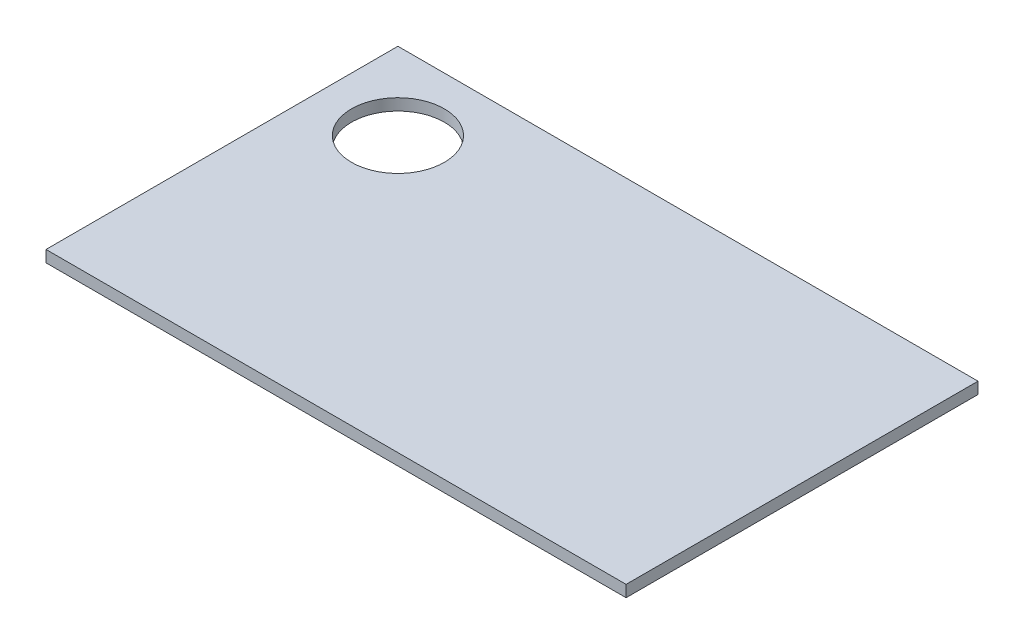
SolidWorks part; units mm, degrees
ref_plane "Front Plane" through (0, 0, 0) normal (0, 0, 1) x (1, 0, 0)
ref_plane "Top Plane" through (0, 0, 0) normal (0, 1, 0) x (1, 0, 0)
ref_plane "Right Plane" through (0, 0, 0) normal (1, 0, 0) x (0, 0, -1)
sketch "Sketch3" plane through (0, 711.2, 0) normal (0, 1, 0) x (1, 0, 0)
  line L0 (-476.25, 298.45) -> (-476.25, -285.75) construction
  line L2 (476.25, 298.45) -> (476.25, -285.75) construction
  line L3 (-476.25, 298.45) -> (476.25, 298.45) construction
  line L4 (-476.25, 298.45) -> (-476.25, -279.4)
  line L5 (-476.25, -279.4) -> (476.25, -279.4)
  line L6 (476.25, 298.45) -> (476.25, -279.4)
  line L7 (-476.25, 298.45) -> (476.25, 298.45)
  line L9 (-438.15, -279.4) -> (-476.25, -279.4) construction
extrude "Boss-Extrude2" add sketch "Sketch3" against normal blind 19.05
sketch "Sketch4" plane through (0, 711.2, 0) normal (0, 1, 0) x (1, 0, 0)
  line L0 (476.25, 298.45) -> (-476.25, 298.45) construction
  line L1 (0, 95.25) -> (0, 0) construction
  line L2 (-203.2, 247.65) -> (203.2, 247.65) construction
  line L3 (-203.2, 247.65) -> (-203.2, 95.25) construction
  line L4 (-203.2, 95.25) -> (203.2, 95.25) construction
  line L5 (203.2, 247.65) -> (203.2, 95.25) construction
  line L6 (-349.25, 171.45) -> (-203.2, 171.45) construction
  line L7 (-476.25, 298.45) -> (-476.25, -279.4) construction
  circle A0 centre (-349.25, 171.45) radius 76.2
  dimension "D1" = 152.4
  dimension "D2" = 127
  dimension "D3" = 152.4
  dimension "D4" = 406.4
  dimension "D5" = 127
extrude "Cut-Extrude1" cut sketch "Sketch4" against normal through all
ref_plane "Filter Plane" through (0, 0, -171.45) normal (0, 0, 1) x (1, 0, 0)
